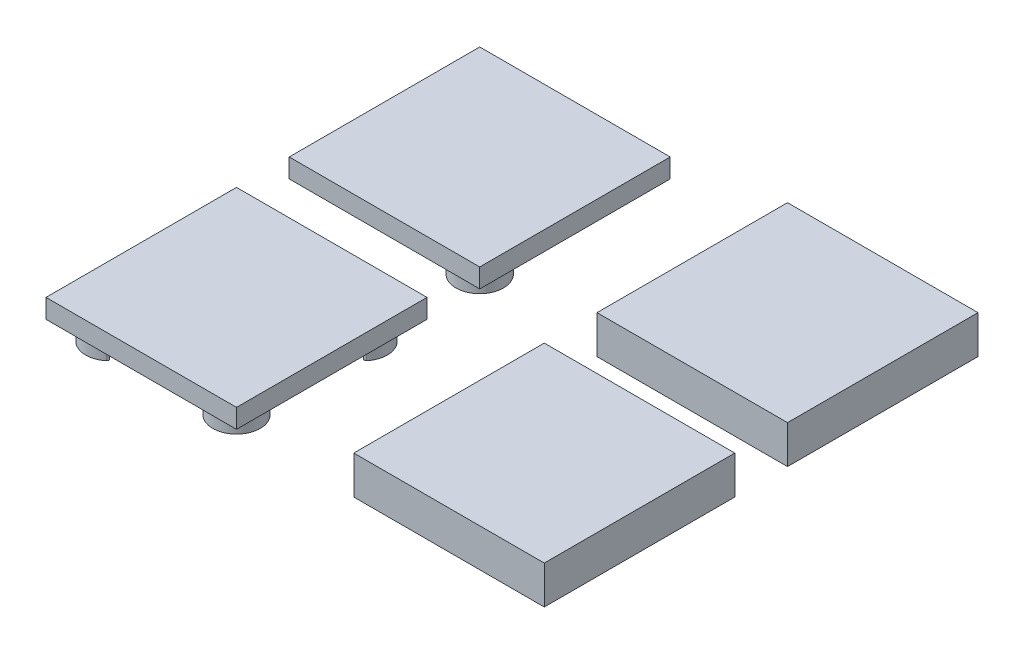
SolidWorks part; units mm, degrees
ref_plane "Front Plane" through (0, 0, 0) normal (0, 0, 1) x (1, 0, 0)
ref_plane "Top Plane" through (0, 0, 0) normal (0, 1, 0) x (1, 0, 0)
ref_plane "Right Plane" through (0, 0, 0) normal (1, 0, 0) x (0, 0, -1)
sketch "Sketch3" plane through (0, 0, 0) normal (0, 1, 0) x (1, 0, 0)
  line L1 (-15, -15) -> (15, -15)
  line L2 (-15, -15) -> (-15, 15)
  line L3 (-15, 15) -> (15, 15)
  line L4 (15, -15) -> (15, 15)
  line L5 (-15, -15) -> (15, 15) construction
  line L6 (-15, 15) -> (15, -15) construction
  point P0 (0, 0)
  dimension "D1" = 30
extrude "Boss-Extrude1" add sketch "Sketch3" along normal blind 3
sketch "Sketch1" plane through (0, 3, 0) normal (0, 1, 0) x (1, 0, 0)
  line L0 (-15, 10) -> (-10, 10) construction
  line L1 (-15, 15) -> (15, 15)
  line L2 (-15, 15) -> (-15, -15)
  line L3 (-15, -15) -> (15, -15)
  line L4 (15, 15) -> (15, -15)
  line L5 (-15, 15) -> (15, -15) construction
  line L6 (-15, -15) -> (15, 15) construction
  line L11 (-12.6517, 7.3483) -> (-7.3483, 12.6517)
  line L12 (7.3483, -12.6517) -> (12.6517, -7.3483)
  arc A1 (-12.6517, 7.3483) -> (-7.3483, 12.6517) centre (-10, 10) cw
  arc A3 (7.3483, -12.6517) -> (12.6517, -7.3483) centre (10, -10) ccw
  point P0 (0, 0)
  dimension "D3" = 5
  dimension "D1" = 3.75
  dimension "D4" = 7.5
  dimension "D5" = 45
extrude "Boss-Extrude2" add sketch "Sketch1" against normal blind 6
sketch "Sketch5" plane through (0, 0, 0) normal (0, 1, 0) x (1, 0, 0)
  line L0 (0, 0) -> (74.9498, 0) construction
  line L1 (63.4658, -15) -> (33.4658, -15)
  line L2 (63.4658, -15) -> (63.4658, 15)
  line L3 (63.4658, 15) -> (33.4658, 15)
  line L4 (33.4658, -15) -> (33.4658, 15)
  line L5 (63.4658, -15) -> (33.4658, 15) construction
  line L6 (63.4658, 15) -> (33.4658, -15) construction
  line L7 (-3.3, 0) -> (3.3, 0) construction
  point P0 (48.4658, 0)
  dimension "D1" = 30
  dimension "D2" = 30
extrude "Boss-Extrude4" add sketch "Sketch5" along normal blind 6 separate body
fillet "Fillet3" radius 0.3 4 edges at (-7.3483, -1.5, -12.6517) (-12.6517, -1.5, -7.3483) (12.6517, -1.5, 7.3483) (7.3483, -1.5, 12.6517)
sketch "Sketch11" plane through (0, 3, 0) normal (0, 1, 0) x (1, 0, 0)
  line L1 (-15, 15) -> (15, 15)
  line L2 (-15, 15) -> (-15, -15)
  line L3 (-15, -15) -> (15, -15)
  line L4 (15, 15) -> (15, -15)
sketch "Sketch16" plane through (0, 6, 0) normal (0, 1, 0) x (1, 0, 0)
  line L0 (33.4658, 10) -> (38.4658, 10) construction
  line L1 (33.4658, 15) -> (63.4658, 15)
  line L2 (33.4658, 15) -> (33.4658, -15)
  line L3 (33.4658, -15) -> (63.4658, -15)
  line L4 (63.4658, 15) -> (63.4658, -15)
  line L5 (33.4658, 15) -> (63.4658, -15) construction
  line L6 (33.4658, -15) -> (63.4658, 15) construction
  line L11 (35.8142, 7.3483) -> (41.1175, 12.6517)
  line L12 (55.8142, -12.6517) -> (61.1175, -7.3483)
  line L13 (35.8142, 12.6517) -> (38.603, 15.4404) construction
  line L14 (35.8151, 7.2078) -> (41.258, 12.6507)
  line L15 (55.6737, -12.6507) -> (61.1166, -7.2078)
  arc A1 (35.8142, 7.3483) -> (41.1175, 12.6517) centre (38.4658, 10) cw
  arc A3 (55.8142, -12.6517) -> (61.1175, -7.3483) centre (58.4658, -10) ccw
  arc A4 (35.8151, 7.2078) -> (41.258, 12.6507) centre (38.4658, 10) cw
  arc A5 (55.6737, -12.6507) -> (61.1166, -7.2078) centre (58.4658, -10) ccw
  point P0 (48.4658, 0)
  dimension "D3" = 5
  dimension "D1" = 3.75
  dimension "D2" = 30
  dimension "D4" = 7.5
  dimension "D5" = 45
  dimension "D6" = 30
  dimension "D7" = 0.1
  dimension "D8" = 0.1
extrude "Cut-Extrude2" cut sketch "Sketch16" against normal blind 3 from offset 3 contours A4 L14 | A5 L15 offset against normal yes
sketch "Sketch17" plane through (0, 0, 0) normal (0, 1, 0) x (1, 0, 0)
  line L0 (15, -15) -> (15, -56.586) construction
  line L1 (-15, -23.3008) -> (15, -23.3008)
  line L2 (-15, -23.3008) -> (-15, -53.3008)
  line L3 (-15, -53.3008) -> (15, -53.3008)
  line L4 (15, -23.3008) -> (15, -53.3008)
  dimension "D1" = 30
  dimension "D2" = 30
extrude "Boss-Extrude6" add sketch "Sketch17" along normal blind 3 separate body
sketch "Sketch19" plane through (0, 3, 0) normal (0, 1, 0) x (1, 0, 0)
  line L0 (-15, -28.3008) -> (-10, -28.3008) construction
  line L1 (-15, -23.3008) -> (15, -23.3008)
  line L2 (-15, -23.3008) -> (-15, -53.3008)
  line L3 (-15, -53.3008) -> (15, -53.3008)
  line L4 (15, -23.3008) -> (15, -53.3008)
  line L5 (-15, -23.3008) -> (15, -53.3008) construction
  line L6 (-15, -53.3008) -> (15, -23.3008) construction
  line L11 (-12.6517, -30.9524) -> (-7.3483, -25.6491)
  line L12 (7.3483, -50.9524) -> (12.6517, -45.6491)
  line L13 (-12.6517, -25.6491) -> (-8.4229, -21.4204) construction
  line L14 (0, -1.65) -> (0, 1.65) construction
  line L15 (-7.3483, -50.9524) -> (-12.6517, -45.6491)
  line L16 (12.6517, -30.9524) -> (7.3483, -25.6491)
  arc A1 (-12.6517, -30.9524) -> (-7.3483, -25.6491) centre (-10, -28.3008) cw
  arc A3 (7.3483, -50.9524) -> (12.6517, -45.6491) centre (10, -48.3008) ccw
  arc A4 (-7.3483, -50.9524) -> (-12.6517, -45.6491) centre (-10, -48.3008) cw
  arc A5 (12.6517, -30.9524) -> (7.3483, -25.6491) centre (10, -28.3008) ccw
  point P0 (0, -38.3008)
  dimension "D3" = 5
  dimension "D1" = 3.75
  dimension "D2" = 30
  dimension "D4" = 7.5
  dimension "D5" = 45
  dimension "D6" = 30
extrude "Boss-Extrude7" add sketch "Sketch19" against normal blind 6 contours L16 A5 | L12 A3 | A4 L15 | L11 A1
sketch "Sketch20" plane through (0, 0, 0) normal (0, 1, 0) x (1, 0, 0)
  line L0 (15, -23.3008) -> (-15, -23.3008) construction
  line L1 (63.4658, -53.3008) -> (33.4658, -53.3008)
  line L2 (63.4658, -53.3008) -> (63.4658, -23.3008)
  line L3 (63.4658, -23.3008) -> (33.4658, -23.3008)
  line L4 (33.4658, -53.3008) -> (33.4658, -23.3008)
  line L5 (63.4658, -53.3008) -> (33.4658, -23.3008) construction
  line L6 (63.4658, -23.3008) -> (33.4658, -53.3008) construction
  line L8 (33.4658, 15) -> (33.4658, -15) construction
  point P0 (48.4658, -38.3008)
  dimension "D1" = 30
  dimension "D2" = 30
extrude "Boss-Extrude8" add sketch "Sketch20" along normal blind 6 separate body
sketch "Sketch21" plane through (0, 6, 0) normal (0, 1, 0) x (1, 0, 0)
  line L0 (33.4658, -28.3008) -> (38.4658, -28.3008) construction
  line L1 (33.4658, -23.3008) -> (63.4658, -23.3008)
  line L2 (33.4658, -23.3008) -> (33.4658, -53.3008)
  line L3 (33.4658, -53.3008) -> (63.4658, -53.3008)
  line L4 (63.4658, -23.3008) -> (63.4658, -53.3008)
  line L5 (33.4658, -23.3008) -> (63.4658, -53.3008) construction
  line L6 (33.4658, -53.3008) -> (63.4658, -23.3008) construction
  line L11 (35.8142, -30.9524) -> (41.1175, -25.6491)
  line L12 (55.8142, -50.9524) -> (61.1175, -45.6491)
  line L13 (35.8142, -25.6491) -> (43.211, -18.2523) construction
  line L14 (58.4658, -28.3008) -> (58.4658, -23.3008) construction
  line L15 (41.1175, -50.9524) -> (35.8142, -45.6491)
  line L16 (61.1175, -30.9524) -> (55.8142, -25.6491)
  line L17 (38.4658, -48.3008) -> (38.4658, -53.3008) construction
  line L21 (55.1279, -50.9316) -> (61.0966, -44.9629)
  line L22 (61.0966, -31.6387) -> (55.1279, -25.67)
  line L23 (41.8037, -50.9316) -> (35.835, -44.9629)
  line L24 (35.835, -31.6387) -> (41.8037, -25.67)
  line L26 (43.4658, -33.3008) -> (43.4658, -43.3008)
  line L27 (53.4658, -33.3008) -> (43.4658, -33.3008)
  line L28 (53.4658, -43.3008) -> (53.4658, -33.3008)
  line L29 (43.4658, -43.3008) -> (53.4658, -43.3008)
  line L30 (43.4658, -33.3008) -> (43.4658, -43.3008)
  line L31 (53.4658, -33.3008) -> (43.4658, -33.3008)
  line L32 (53.4658, -43.3008) -> (53.4658, -33.3008)
  line L33 (43.4658, -43.3008) -> (53.4658, -43.3008)
  arc A1 (35.8142, -30.9524) -> (41.1175, -25.6491) centre (38.4658, -28.3008) cw
  arc A3 (55.8142, -50.9524) -> (61.1175, -45.6491) centre (58.4658, -48.3008) ccw
  arc A4 (41.1175, -50.9524) -> (35.8142, -45.6491) centre (38.4658, -48.3008) cw
  arc A5 (61.1175, -30.9524) -> (55.8142, -25.6491) centre (58.4658, -28.3008) ccw
  arc A6 (61.0966, -31.6387) -> (55.1279, -25.67) centre (58.4658, -28.3008) ccw
  arc A10 (55.1279, -50.9316) -> (61.0966, -44.9629) centre (58.4658, -48.3008) ccw
  arc A11 (41.8037, -50.9316) -> (35.835, -44.9629) centre (38.4658, -48.3008) cw
  arc A12 (35.835, -31.6387) -> (41.8037, -25.67) centre (38.4658, -28.3008) cw
  point P0 (48.4658, -38.3008)
  point P15 (61.1175, -25.6491)
  point P16 (35.8142, -50.9524)
  point P45 (48.5365, -38.2301)
  dimension "D3" = 5
  dimension "D1" = 3.75
  dimension "D2" = 30
  dimension "D4" = 7.5
  dimension "D5" = 45
  dimension "D6" = 30
  dimension "D7" = 5
  dimension "D8" = 5
  dimension "D9" = 3.75
  dimension "D10" = 3.75
  dimension "D11" = 7.5
  dimension "D12" = 7.5
  dimension "D13" = 45
  dimension "D14" = 45
  dimension "D15" = 10
  dimension "D16" = 0.5
  dimension "D17" = 0.5
  dimension "D18" = 0.5
  dimension "D19" = 0.5
extrude "Cut-Extrude3" cut sketch "Sketch21" against normal blind 3 from offset 3 offset against normal yes
sketch "Sketch4" plane through (0, 3, 0) normal (0, 1, 0) x (1, 0, 0)
  line L1 (-15, 15) -> (15, 15)
  line L2 (-15, 15) -> (-15, -15)
  line L3 (-15, -15) -> (15, -15)
  line L4 (15, 15) -> (15, -15)
  line L5 (-15, 15) -> (15, -15) construction
  line L6 (-15, -15) -> (15, 15) construction
  point P0 (0, 0)
fillet "Fillet4" radius 0.3 4 edges at (61.1166, 1.5, 7.2078) (55.6737, 1.5, 12.6507) (41.258, 1.5, -12.6507) (35.8151, 1.5, -7.2078)
fillet "Fillet5" radius 0.3 8 edges at (-7.3483, -1.5, 50.9524) (-12.6517, -1.5, 45.6491) (-12.6517, -1.5, 30.9524) (-7.3483, -1.5, 25.6491) (12.6517, -1.5, 30.9524) (7.3483, -1.5, 25.6491) (7.3483, -1.5, 50.9524) (12.6517, -1.5, 45.6491)
fillet "Fillet6" radius 0.3 8 edges at (61.0966, 1.5, 31.6387) (55.1279, 1.5, 25.67) (41.8037, 1.5, 25.67) (35.835, 1.5, 31.6387) (35.835, 1.5, 44.9629) (41.8037, 1.5, 50.9316) (55.1279, 1.5, 50.9316) (61.0966, 1.5, 44.9629)
